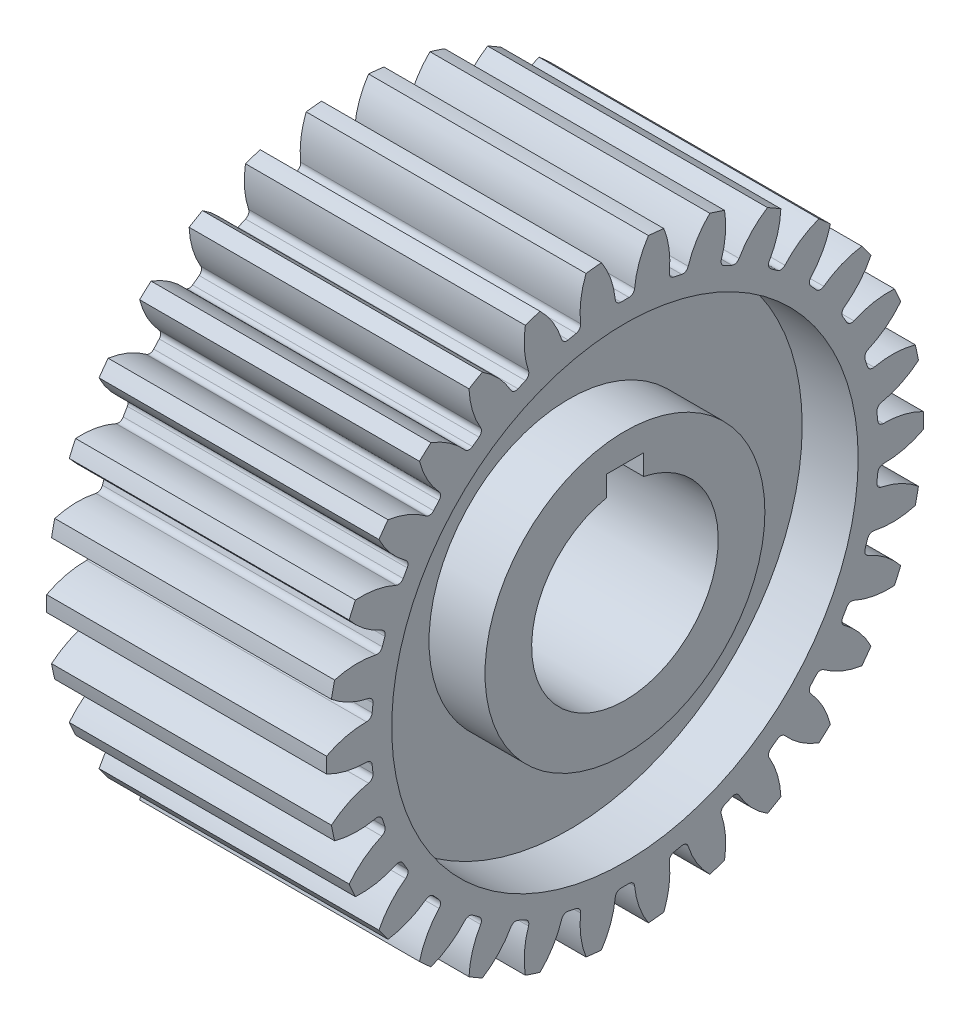
SolidWorks part; units mm, degrees
ref_plane "Front Plane" through (0, 0, 0) normal (0, 0, 1) x (1, 0, 0)
ref_plane "Top Plane" through (0, 0, 0) normal (0, 1, 0) x (1, 0, 0)
ref_plane "Right Plane" through (0, 0, 0) normal (1, 0, 0) x (0, 0, -1)
sketch "Sketch1" plane through (0, 0, 0) normal (1, 0, 0) x (0, 0, -1)
  circle A0 centre (0, 0) radius 16
  dimension "D1" = 32
extrude "Boss-Extrude1" add sketch "Sketch1" along normal mid plane 15
sketch "Sketch2" plane through (7.5, 0, 0) normal (1, 0, 0) x (0, 0, -1)
  line L2 (-1, 4.899) -> (-1, 6)
  line L3 (-1, 6) -> (1, 6)
  line L4 (1, 4.899) -> (1, 6)
  arc A0 (-1, 4.899) -> (1, 4.899) centre (0, 0) ccw
  point P3 (0, 5)
  dimension "D1" = 10
  dimension "D2" = 2
extrude "Cut-Extrude1" cut sketch "Sketch2" against normal through all contours A0 L4 L3 L2
sketch "Sketch3" plane through (7.5, 0, 0) normal (1, 0, 0) x (0, 0, -1)
  circle A0 centre (0, 0) radius 12.5
  circle A1 centre (0, 0) radius 7.5
  dimension "D1" = 15
  dimension "D2" = 25
extrude "Cut-Extrude2" cut sketch "Sketch3" against normal blind 3
mirror "Mirror1" about plane through (0, 0, 0) normal (1, 0, 0) of "Cut-Extrude2"
sketch "Sketch4" plane through (7.5, 0, 0) normal (1, 0, 0) x (0, 0, -1)
  line L0 (0, 0) -> (0, 19.0911) construction
  line L1 (-0.2199, 13.6) -> (0.2199, 13.6)
  arc A0 (0.5184, 13.8707) -> (2.08, 16.88) centre (5.0567, 13.4256) cw
  arc A1 (-0.5184, 13.8707) -> (-2.08, 16.88) centre (-5.0567, 13.4256) ccw
  arc A2 (-2.08, 16.88) -> (2.08, 16.88) centre (0, -0.9994) cw
  arc A3 (0.2199, 13.6) -> (0.5184, 13.8707) centre (0.2199, 13.9) ccw
  arc A4 (-0.5184, 13.8707) -> (-0.2199, 13.6) centre (-0.2199, 13.9) ccw
  point P9 (0.5, 13.6)
  point P14 (0, 13.6)
  point P16 (-0.5, 13.6)
  dimension "D5" = 4.56
  dimension "D6" = 18
  dimension "D7" = 0.3
  dimension "D1" = 0.5
  dimension "D2" = 13.6
  dimension "D3" = 1.58
  dimension "D4" = 3.28
extrude "Cut-Extrude3" cut sketch "Sketch4" against normal through all
pattern_circular "CirPattern2" count 30 over 360 about axis through (0, 0, 0) along (1, 0, 0) of "Cut-Extrude3"
